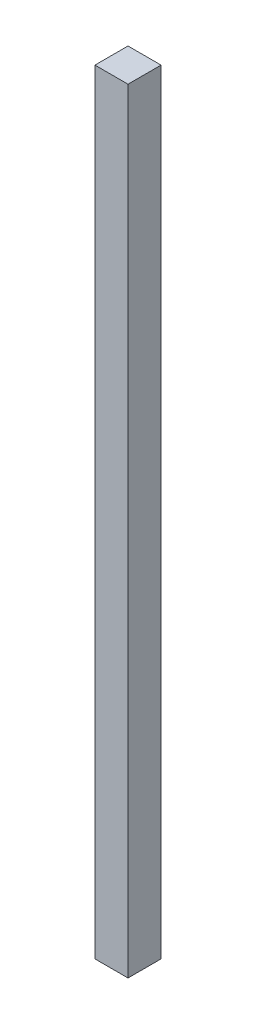
SolidWorks part; units mm, degrees
ref_plane "Front Plane" through (0, 0, 0) normal (0, 0, 1) x (1, 0, 0)
ref_plane "Top Plane" through (0, 0, 0) normal (0, 1, 0) x (1, 0, 0)
ref_plane "Right Plane" through (0, 0, 0) normal (1, 0, 0) x (0, 0, -1)
sketch "Sketch1" plane through (0, 0, 0) normal (0, 1, 0) x (1, 0, 0)
  line L1 (0, 0) -> (25.4, 0)
  line L2 (0, 0) -> (0, 25.4)
  line L3 (0, 25.4) -> (25.4, 25.4)
  line L4 (25.4, 0) -> (25.4, 25.4)
  dimension "D1" = 25.4
  dimension "D2" = 25.4
extrude "Boss-Extrude1" add sketch "Sketch1" along normal blind 609.6
sketch "Sketch3" plane through (0, 0, -25.4) normal (0, 0, -1) x (-1, 0, 0)
  line L0 (0, 609.6) -> (0, 0) construction
  line L1 (0, 487.5018) -> (-25.4, 487.5018)
  line L2 (0, 487.5018) -> (0, 609.6)
  line L3 (0, 609.6) -> (-25.4, 609.6)
  line L4 (-25.4, 487.5018) -> (-25.4, 609.6)
  line L5 (0, 487.5018) -> (-25.4, 487.5018) construction
extrude "Cut-Extrude1" [suppressed] cut sketch "Sketch3" against normal up to surface (25.4 mm away)
sketch "Sketch4" [suppressed] plane through (0, 0, 0) normal (0, 0, 1) x (1, 0, 0)
  line L0 (0, 609.6) -> (0, 0) construction
  line L1 (0, 297.6179) -> (25.4, 297.6179)
  line L2 (0, 297.6179) -> (0, 609.6)
  line L3 (0, 609.6) -> (25.4, 609.6)
  line L4 (25.4, 297.6179) -> (25.4, 609.6)
  line L5 (25.4, 297.6179) -> (0, 297.6179) construction
extrude "Cut-Extrude2" [suppressed] cut sketch "Sketch4" against normal up to surface (25.4 mm away)
sketch "Sketch5" plane through (0, 0, -25.4) normal (0, 0, -1) x (-1, 0, 0)
  line L0 (0, 609.6) -> (0, 0) construction
  line L1 (0, 594.529) -> (-25.4, 594.529)
  line L2 (0, 594.529) -> (0, 609.6)
  line L3 (0, 609.6) -> (-25.4, 609.6)
  line L4 (-25.4, 594.529) -> (-25.4, 609.6)
  line L5 (0, 594.529) -> (-25.4, 594.529) construction
extrude "Cut-Extrude3" cut sketch "Sketch5" against normal up to surface (25.4 mm away) up to face at (12.7, 304.8, 0)
sketch "Sketch6" [suppressed] plane through (0, 0, -25.4) normal (0, 0, -1) x (-1, 0, 0)
  line L0 (0, 609.6) -> (0, 0) construction
  line L1 (0, 574.651) -> (-25.4, 574.651)
  line L2 (0, 574.651) -> (0, 609.6)
  line L3 (0, 609.6) -> (-25.4, 609.6)
  line L4 (-25.4, 574.651) -> (-25.4, 609.6)
  line L5 (0, 574.651) -> (-25.4, 574.651) construction
extrude "Cut-Extrude4" [suppressed] cut sketch "Sketch6" against normal up to surface (25.4 mm away)
sketch "Sketch7" [suppressed] plane through (0, 0, 0) normal (0, 0, 1) x (1, 0, 0)
  line L0 (25.4, 609.6) -> (25.4, 0) construction
  line L1 (25.4, 443.1645) -> (0, 443.1645)
  line L2 (25.4, 443.1645) -> (25.4, 609.6)
  line L3 (25.4, 609.6) -> (0, 609.6)
  line L4 (0, 443.1645) -> (0, 609.6)
  line L5 (25.4, 443.1645) -> (0, 443.1645) construction
extrude "Cut-Extrude5" [suppressed] cut sketch "Sketch7" against normal up to surface (25.4 mm away)
sketch "Sketch8" [suppressed] plane through (0, 0, -25.4) normal (0, 0, -1) x (-1, 0, 0)
  line L0 (0, 609.6) -> (0, 0) construction
  line L1 (0, 340.2572) -> (-25.4, 340.2572)
  line L2 (0, 340.2572) -> (0, 609.6)
  line L3 (0, 609.6) -> (-25.4, 609.6)
  line L4 (-25.4, 340.2572) -> (-25.4, 609.6)
  line L5 (0, 340.2572) -> (-25.4, 340.2572) construction
extrude "Cut-Extrude6" [suppressed] cut sketch "Sketch8" against normal up to surface (25.4 mm away)
sketch "Sketch9" [suppressed] plane through (0, 0, 0) normal (0, 0, 1) x (1, 0, 0)
  line L0 (0, 609.6) -> (0, 0) construction
  line L1 (0, 350.8333) -> (25.4, 350.8333)
  line L2 (0, 350.8333) -> (0, 609.6)
  line L3 (0, 609.6) -> (25.4, 609.6)
  line L4 (25.4, 350.8333) -> (25.4, 609.6)
  line L5 (25.4, 350.8333) -> (0, 350.8333) construction
extrude "Cut-Extrude7" [suppressed] cut sketch "Sketch9" against normal up to surface (25.4 mm away)
